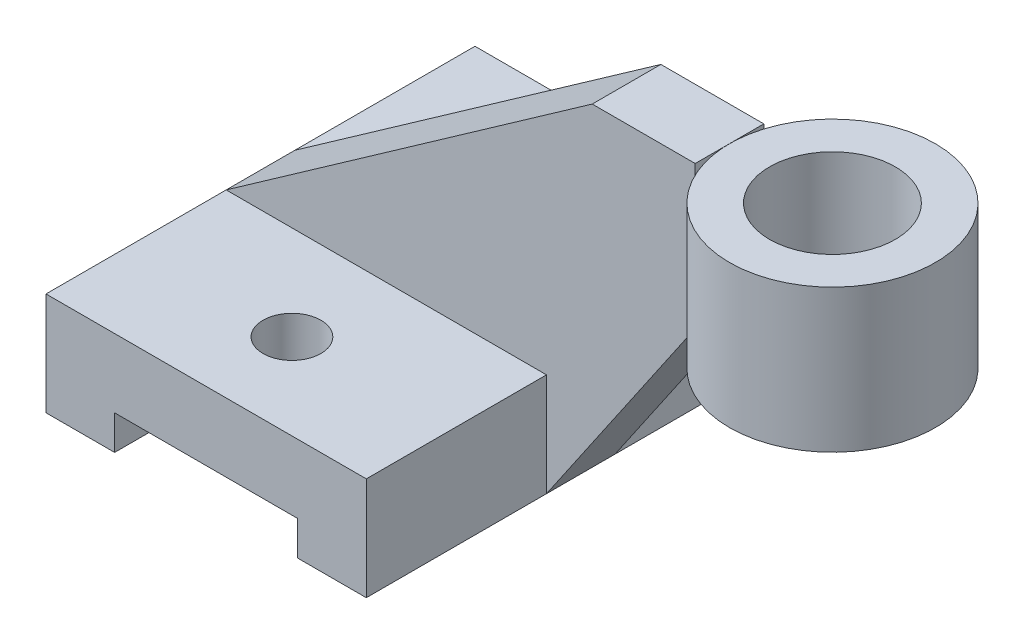
SolidWorks part; units mm, degrees
ref_plane "Front Plane" through (0, 0, 0) normal (0, 0, 1) x (1, 0, 0)
ref_plane "Top Plane" through (0, 0, 0) normal (0, 1, 0) x (1, 0, 0)
ref_plane "Right Plane" through (0, 0, 0) normal (1, 0, 0) x (0, 0, -1)
sketch "Sketch1" plane through (0, 0, 0) normal (0, 1, 0) x (1, 0, 0)
  line L1 (-28, -37.5) -> (28, -37.5)
  line L2 (-28, -37.5) -> (-28, 37.5)
  line L3 (-28, 37.5) -> (28, 37.5)
  line L4 (28, -37.5) -> (28, 37.5)
  line L5 (-28, -37.5) -> (28, 37.5) construction
  line L6 (-28, 37.5) -> (28, -37.5) construction
  point P0 (0, 0)
  dimension "D1" = 75
  dimension "D2" = 56
extrude "Boss-Extrude1" add sketch "Sketch1" along normal blind 18
sketch "Sketch2" plane through (0, 0, 37.5) normal (0, 0, 1) x (1, 0, 0)
  line L0 (-28, 0) -> (28, 0) construction
  line L1 (-16, 0) -> (16, 0)
  line L2 (-16, 0) -> (-16, 6)
  line L3 (-16, 6) -> (16, 6)
  line L4 (16, 0) -> (16, 6)
  point P6 (0, 6)
  dimension "D1" = 6
  dimension "D2" = 32
extrude "Cut-Extrude1" cut sketch "Sketch2" against normal through all
sketch "Sketch3" plane through (0, 18, 0) normal (0, 1, 0) x (1, 0, 0)
  line L0 (-28, 37.5) -> (-28, -37.5) construction
  line L1 (-28, -37.5) -> (28, -37.5) construction
  line L2 (28, 37.5) -> (-28, 37.5) construction
  circle A0 centre (0, -22.5) radius 5.0558
  circle A1 centre (0, 22.5) radius 5.631
  dimension "D1" = 28
  dimension "D2" = 15
  dimension "D3" = 15
  dimension "D4" = 45
extrude "Cut-Extrude2" cut sketch "Sketch3" against normal through all
ref_plane "Plane1" through (0, 0, 6) normal (0, 0, 1) x (1, 0, 0)
sketch "Sketch4" plane through (0, 0, 6) normal (0, 0, 1) x (1, 0, 0)
  line L0 (-28, 18) -> (36, 63)
  line L6 (-28, 18) -> (36, 18)
  line L7 (36, 18) -> (36, 63)
  point P1 (0, 0)
  point P9 (35.1185, 63)
  dimension "D2" = 64
  dimension "D4" = 45
extrude "Boss-Extrude2" add sketch "Sketch4" against normal blind 12
ref_plane "Plane2" through (0, 63, 0) normal (0, 1, 0) x (0, 0, 1)
sketch "Sketch8" plane through (0, 63, 0) normal (0, 1, 0) x (0, 0, 1)
  line L0 (-6, 36) -> (6, 36) construction
  circle A0 centre (0, 72) radius 18
  circle A1 centre (0, 72) radius 11
  dimension "D1" = 36
  dimension "D2" = 22
  dimension "D3" = 36
extrude "Boss-Extrude3" add sketch "Sketch8" against normal blind 25 separate body
sketch "Sketch9" plane through (0, 0, 6) normal (0, 0, 1) x (1, 0, 0)
  line L0 (36, 63) -> (54, 63)
  line L1 (54, 38) -> (28, 0)
  line L2 (36, 63) -> (36, 18)
  line L3 (36, 18) -> (28, 18)
  line L4 (28, 18) -> (28, 0)
  line L5 (54, 63) -> (54, 38)
extrude "Boss-Extrude4" add sketch "Sketch9" against normal blind 12
